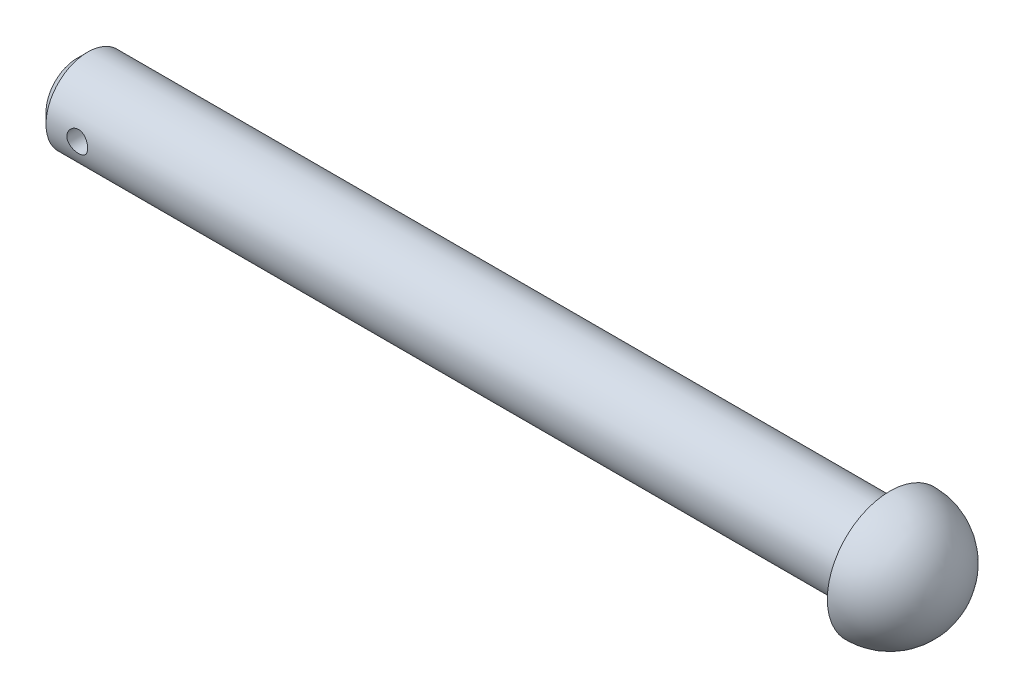
SolidWorks part; units mm, degrees
ref_plane "Front Plane" through (0, 0, 0) normal (0, 0, 1) x (1, 0, 0)
ref_plane "Top Plane" through (0, 0, 0) normal (0, 1, 0) x (1, 0, 0)
ref_plane "Right Plane" through (0, 0, 0) normal (1, 0, 0) x (0, 0, -1)
sketch "Sketch2" plane through (0, 0, 0) normal (0, 0, 1) x (1, 0, 0)
  line L0 (39, 2) -> (39, 3)
  line L1 (0, 0) -> (39, 0)
  line L2 (0, 0) -> (0, 2)
  line L3 (0, 2) -> (39, 2)
  line L5 (39, 0) -> (42, 0)
  arc A0 (42, 0) -> (39, 3) centre (39, 0) ccw
  dimension "D2" = 3
  dimension "D1" = 2
  dimension "D3" = 39
revolve "Revolve1" add sketch "Sketch2" angle 360 about L1
sketch "Sketch3" plane through (0, 0, 0) normal (0, 0, 1) x (1, 0, 0)
  circle A0 centre (2, 0) radius 0.5
  point P2 (0, 0)
  dimension "D2" = 1
  dimension "D1" = 2
extrude "Cut-Extrude1" cut sketch "Sketch3" against normal through all both and the other way through all
chamfer "Chamfer1" distance 0.5 angle 45 1 edges at (0, 0, 2)
